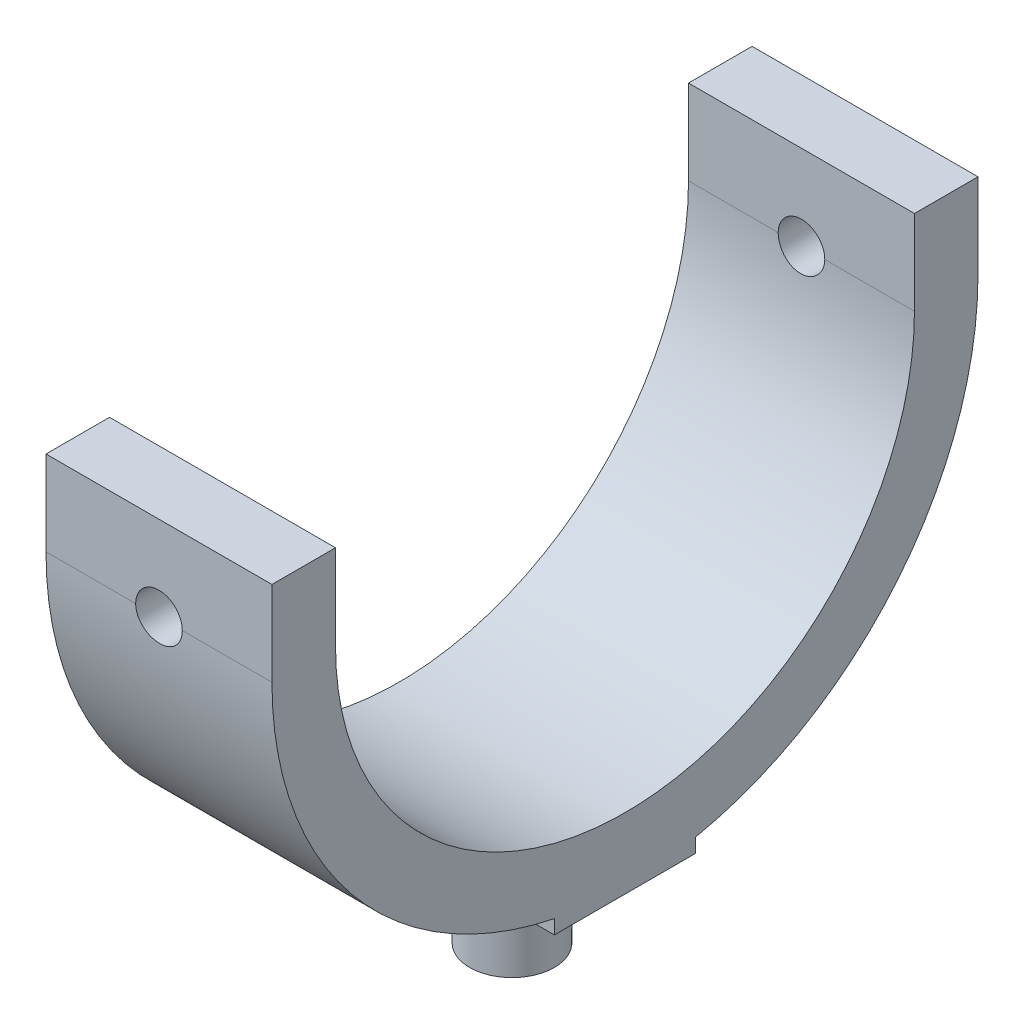
SolidWorks part; units mm, degrees
ref_plane "Front Plane" through (0, 0, 0) normal (0, 0, 1) x (1, 0, 0)
ref_plane "Top Plane" through (0, 0, 0) normal (0, 1, 0) x (1, 0, 0)
ref_plane "Right Plane" through (0, 0, 0) normal (1, 0, 0) x (0, 0, -1)
sketch "Sketch1" plane through (0, 0, 0) normal (1, 0, 0) x (0, 0, -1)
  line L3 (-5, -24.4949) -> (-5, -25.4949)
  line L4 (-5, -25.4949) -> (5, -25.4949)
  line L5 (5, -24.4949) -> (5, -25.4949)
  line L8 (25, 0) -> (25, 6)
  line L9 (25, 6) -> (20.5, 6)
  line L10 (20.5, 0) -> (20.5, 6)
  line L12 (-20.5, 0) -> (-20.5, 6)
  line L13 (-20.5, 6) -> (-25, 6)
  line L14 (-25, 0) -> (-25, 6)
  arc A0 (-25, 0) -> (-5, -24.4949) centre (0, 0) ccw
  arc A1 (5, -24.4949) -> (25, 0) centre (0, 0) ccw
  arc A2 (-20.5, 0) -> (20.5, 0) centre (0, 0) ccw
  dimension "D1" = 25
  dimension "D4" = 41
  dimension "D2" = 10
  dimension "D3" = 1
  dimension "D5" = 6
extrude "Boss-Extrude1" add sketch "Sketch1" along normal blind 16
sketch "Sketch4" plane through (0, -25.4949, 0) normal (0, -1, 0) x (1, 0, 0)
  line L0 (16, 5) -> (0, 5) construction
  line L1 (0, 5) -> (0, -5) construction
  circle A0 centre (8, 0) radius 3
  point P5 (8, 5)
  point P9 (0, 0)
  dimension "D1" = 6
extrude "Boss-Extrude2" add sketch "Sketch4" along normal blind 7
sketch "Sketch5" plane through (0, 0, -25) normal (0, 0, -1) x (-1, 0, 0)
  line L0 (-16, 0) -> (0, 0) construction
  circle A0 centre (-8, 0) radius 1.65
  dimension "D1" = 3.3
extrude "Cut-Extrude1" cut sketch "Sketch5" against normal through all
